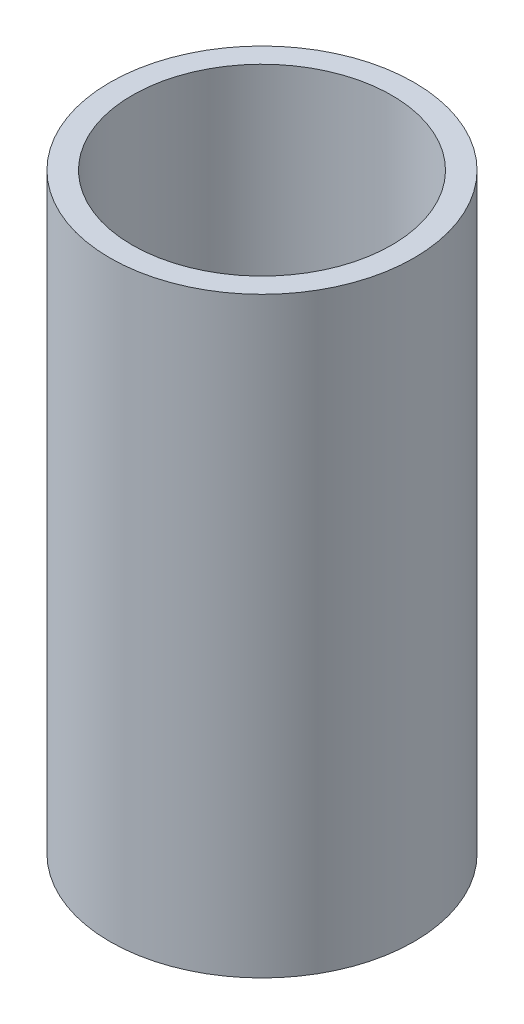
SolidWorks part; units mm, degrees
ref_plane "Front Plane" through (0, 0, 0) normal (0, 0, 1) x (1, 0, 0)
ref_plane "Top Plane" through (0, 0, 0) normal (0, 1, 0) x (1, 0, 0)
ref_plane "Right Plane" through (0, 0, 0) normal (1, 0, 0) x (0, 0, -1)
sketch "Sketch1" plane through (0, 0, 0) normal (0, 1, 0) x (1, 0, 0)
  circle A0 centre (0, 0) radius 8
  dimension "D1" = 16
extrude "Extrude-Thin1" add sketch "Sketch1" along normal blind 36.5 thin
